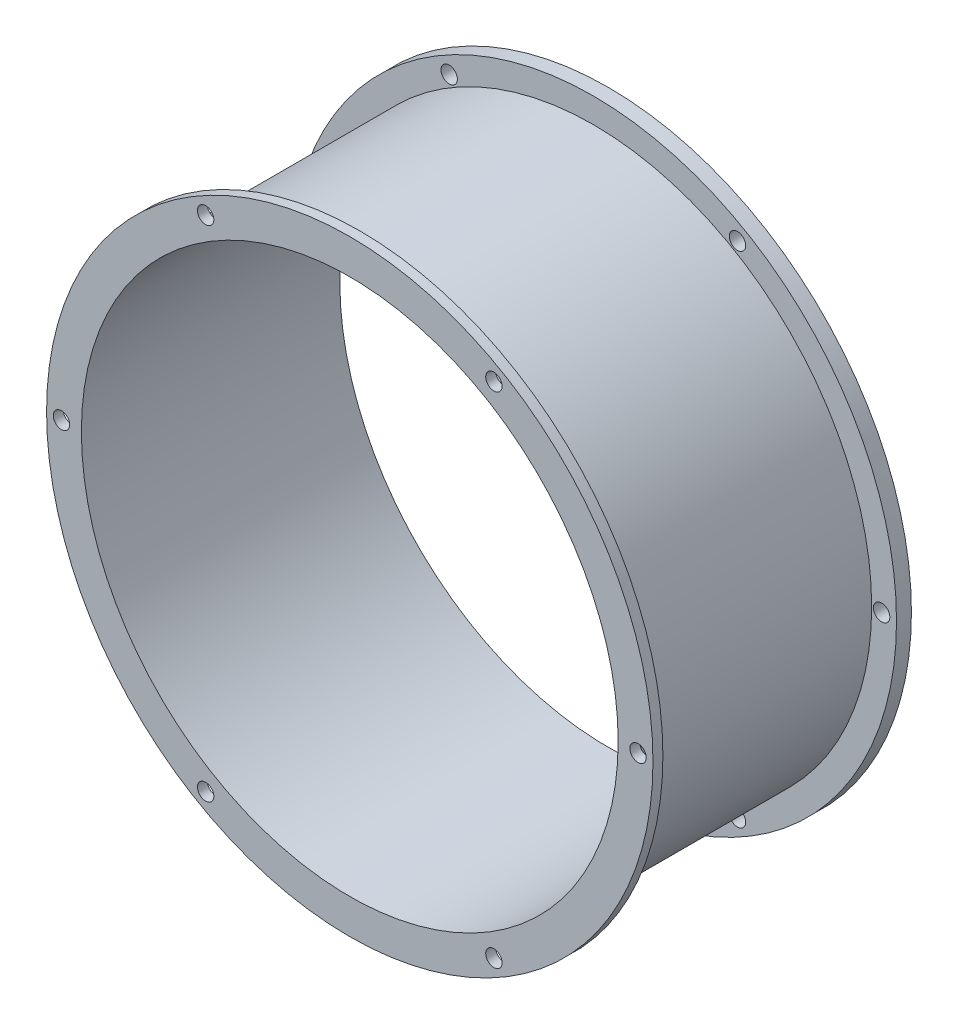
SolidWorks part; units mm, degrees
ref_plane "Спереди" through (0, 0, 0) normal (0, 0, 1) x (1, 0, 0)
ref_plane "Сверху" through (0, 0, 0) normal (0, 1, 0) x (1, 0, 0)
ref_plane "Справа" through (0, 0, 0) normal (1, 0, 0) x (0, 0, -1)
sketch "Эскиз1" plane through (0, 0, 0) normal (0, 0, 1) x (1, 0, 0)
  circle A0 centre (0, 0) radius 56
  circle A1 centre (0, 0) radius 54
extrude "Jacket" add sketch "Эскиз1" along normal blind 52 from offset 32
sketch "Эскиз2" plane through (0, 0, 0) normal (0, 0, 1) x (1, 0, 0)
  circle A0 centre (0, 0) radius 61
  circle A1 centre (0, 0) radius 54
extrude "Rear_flange" add sketch "Эскиз2" along normal blind 3 from offset 32
sketch "Эскиз3" plane through (0, 0, 0) normal (0, 0, 1) x (1, 0, 0)
  circle A0 centre (0, 0) radius 61
  circle A1 centre (0, 0) radius 54
extrude "Front_flange" add sketch "Эскиз3" along normal blind 2 from offset 18
sketch "Эскиз4" plane through (0, 0, 0) normal (0, 0, 1) x (1, 0, 0)
  circle A0 centre (58, 0) radius 1.65
  circle A1 centre (29, 50.2295) radius 1.65
  circle A2 centre (-29, 50.2295) radius 1.65
  circle A3 centre (-58, 0) radius 1.65
  circle A4 centre (-29, -50.2295) radius 1.65
  circle A5 centre (29, -50.2295) radius 1.65
extrude "Through_holes" cut sketch "Эскиз4" against normal mid plane 200
